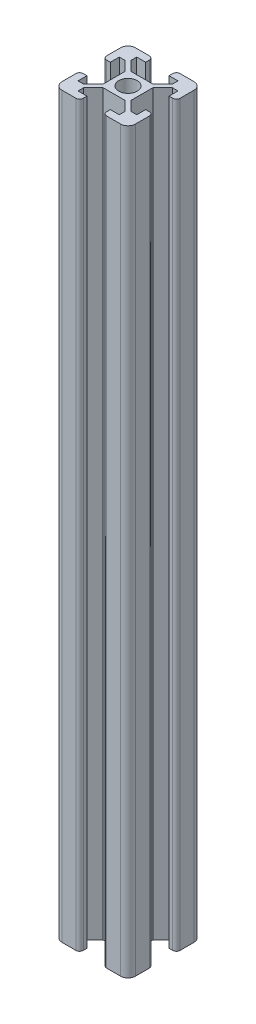
SolidWorks part; units mm, degrees
material "2024 合金"
ref_plane "前视基准面" through (0, 0, 0) normal (0, 0, 1) x (1, 0, 0)
ref_plane "上视基准面" through (0, 0, 0) normal (0, 1, 0) x (1, 0, 0)
ref_plane "右视基准面" through (0, 0, 0) normal (1, 0, 0) x (0, 0, -1)
sketch "草图1" plane through (0, 0, 0) normal (0, 1, 0) x (1, 0, 0)
  line L0 (9.95, -9.95) -> (5.59, -9.95)
  line L1 (-9.95, -9.95) -> (9.95, -9.95)
  line L2 (-9.95, -9.95) -> (-9.95, 9.95)
  line L3 (-9.95, 9.95) -> (9.95, 9.95)
  line L4 (9.95, -9.95) -> (9.95, 9.95)
  line L5 (-9.95, -9.95) -> (9.95, 9.95) construction
  line L6 (-9.95, 9.95) -> (9.95, -9.95) construction
  line L7 (-3.8, 3.8) -> (3.8, 3.8)
  line L8 (-3.8, 3.8) -> (-3.8, -3.8)
  line L9 (-3.8, -3.8) -> (3.8, -3.8)
  line L10 (3.8, 3.8) -> (3.8, -3.8)
  line L11 (-3.8, 3.8) -> (3.8, -3.8) construction
  line L12 (-3.8, -3.8) -> (3.8, 3.8) construction
  line L13 (9.95, 9.95) -> (5.59, 9.95)
  line L14 (9.95, 9.95) -> (9.95, 5.59)
  line L15 (9.95, 5.59) -> (5.59, 5.59)
  line L16 (5.59, 9.95) -> (5.59, 5.59)
  line L17 (9.95, -9.95) -> (9.95, -5.59)
  line L18 (9.95, -5.59) -> (5.59, -5.59)
  line L19 (5.59, -9.95) -> (5.59, -5.59)
  line L20 (-9.95, -9.95) -> (-9.95, -5.59)
  line L21 (-9.95, -9.95) -> (-5.59, -9.95)
  line L22 (-5.59, -9.95) -> (-5.59, -5.59)
  line L23 (-9.95, -5.59) -> (-5.59, -5.59)
  line L24 (-9.95, 9.95) -> (-5.59, 9.95)
  line L25 (-9.95, 9.95) -> (-9.95, 5.59)
  line L26 (-9.95, 5.59) -> (-5.59, 5.59)
  line L27 (-5.59, 9.95) -> (-5.59, 5.59)
  line L28 (-9.95, -9.1015) -> (9.1015, 9.95)
  line L29 (9.95, 9.1015) -> (-9.1015, -9.95)
  line L30 (-9.95, 9.1015) -> (9.1015, -9.95)
  line L31 (9.95, -9.1015) -> (-9.1015, 9.95)
  line L32 (9.95, 9.95) -> (7.95, 9.95)
  line L33 (-9.95, 9.95) -> (-7.95, 9.95)
  line L34 (-9.95, 9.95) -> (-9.95, 3.17)
  line L35 (-9.95, 3.17) -> (-7.95, 3.17)
  line L36 (-7.95, 9.95) -> (-7.95, 3.17)
  line L37 (-9.95, 9.95) -> (-3.17, 9.95)
  line L38 (-9.95, 9.95) -> (-9.95, 7.95)
  line L39 (-9.95, 7.95) -> (-3.17, 7.95)
  line L40 (-3.17, 9.95) -> (-3.17, 7.95)
  line L41 (9.95, 9.95) -> (9.95, 3.17)
  line L42 (9.95, 3.17) -> (7.95, 3.17)
  line L43 (7.95, 9.95) -> (7.95, 3.17)
  line L44 (9.95, 9.95) -> (3.17, 9.95)
  line L45 (9.95, 9.95) -> (9.95, 7.95)
  line L46 (9.95, 7.95) -> (3.17, 7.95)
  line L47 (3.17, 9.95) -> (3.17, 7.95)
  line L48 (9.95, -9.95) -> (9.95, -7.95)
  line L49 (9.95, -9.95) -> (3.17, -9.95)
  line L50 (3.17, -9.95) -> (3.17, -7.95)
  line L51 (9.95, -7.95) -> (3.17, -7.95)
  line L52 (9.95, -9.95) -> (9.95, -3.17)
  line L53 (9.95, -9.95) -> (7.95, -9.95)
  line L54 (7.95, -9.95) -> (7.95, -3.17)
  line L55 (9.95, -3.17) -> (7.95, -3.17)
  line L56 (-9.95, -9.95) -> (-7.95, -9.95)
  line L57 (-9.95, -9.95) -> (-9.95, -3.17)
  line L58 (-9.95, -3.17) -> (-7.95, -3.17)
  line L59 (-7.95, -9.95) -> (-7.95, -3.17)
  line L60 (-9.95, -9.95) -> (-3.17, -9.95)
  line L61 (-9.95, -9.95) -> (-9.95, -7.95)
  line L62 (-9.95, -7.95) -> (-3.17, -7.95)
  line L63 (-3.17, -9.95) -> (-3.17, -7.95)
  circle A0 centre (0, 0) radius 2.5
  point P0 (0, 0)
  point P18 (0, 0)
  point P23 (0, 0)
  point P28 (0, 0)
  point P33 (0, 0)
  point P69 (0, 0)
  dimension "D3" = 5
  dimension "D1" = 19.9
  dimension "D2" = 19.9
  dimension "D4" = 7.6
  dimension "D5" = 7.6
  dimension "D6" = 4.36
  dimension "D8" = 1.2
  dimension "D9" = 1.2
  dimension "D10" = 6.78
  dimension "D11" = 2
  dimension "D12" = 6.78
  dimension "D13" = 2
  dimension "D7" = 4
  dimension "D14" = 4
extrude "凸台-拉伸1" add sketch "草图1" along normal blind 200 contours L40 L3 L27 L39 | L31 L39 L27 L3 L36 | L36 L24 L31 | L30 L39 L36 L31 L3 L25 | L34 L39 L30 | L39 L2 L26 L36 L30 | L36 L39 L31 | L39 L30 L36 | L36 L26 L2 L35 | L39 L31 L27 | L39 L36 L30 L26 L27 L31 | L30 L36 L26 | L7 L31 L27 L26 L30 L8 | L3 L47 L46 L16 | L46 L28 L43 L3 L16 | L13 L43 L28 | L46 L29 L14 L13 L28 L43 | L46 L41 L29 | L4 L46 L29 L43 L15 | L46 L43 L28 | L29 L46 L43 | L15 L43 L42 L4 | L43 L46 L28 L16 L15 L29 | L43 L29 L15 | L28 L46 L16 | L29 L15 L16 L28 L7 L10 | L4 L55 L54 L18 | L54 L31 L51 L4 L18 | L17 L51 L31 | L54 L30 L0 L4 L31 L51 | L54 L1 L30 | L54 L51 L31 | L30 L54 L51 | L49 L54 L30 L51 L19 | L19 L51 L50 L1 | L51 L30 L19 | L51 L54 L31 L18 L19 L30 | L31 L54 L18 | L23 L59 L58 L2 | L57 L62 L28 L59 L23 | L59 L28 L23 | L59 L62 L29 L22 L23 L28 | L29 L62 L22 | L62 L29 L59 L1 L22 | L1 L63 L62 L22 | L62 L59 L29 | L28 L62 L59 | L62 L28 L2 L1 L29 L59 | L62 L20 L28 | L21 L59 L29 | L29 L9 L8 L28 L23 L22 | L18 L31 L10 L9 L30 L19 | A0 L31 L10 L29 | A0 L28 L7 L31 | A0 L30 L8 L28 | A0 L29 L9 L30 | A0 L28 L8 L9 L29 | A0 L30 L9 L10 L31 | A0 L29 L10 L7 L28 | A0 L31 L7 L8 L30
fillet "圆角1" radius 2 4 edges at (9.95, 100, -9.95) (9.95, 100, 9.95) (-9.95, 100, 9.95) (-9.95, 100, -9.95)
fillet "圆角2" radius 1 8 edges at (3.17, 100, -9.95) (-3.17, 100, -9.95) (9.95, 100, 3.17) (9.95, 100, -3.17) (3.17, 100, 9.95) (-3.17, 100, 9.95) (-9.95, 100, -3.17) (-9.95, 100, 3.17)
